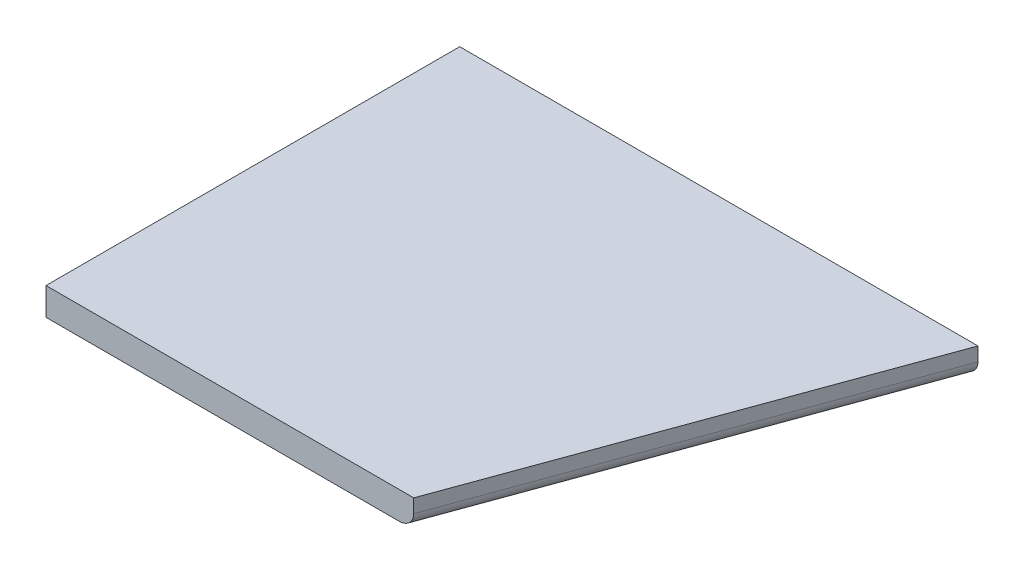
SolidWorks part; units mm, degrees
ref_plane "Front" through (0, 0, 0) normal (0, 0, 1) x (1, 0, 0)
ref_plane "Top" through (0, 0, 0) normal (0, 1, 0) x (1, 0, 0)
ref_plane "Right" through (0, 0, 0) normal (1, 0, 0) x (0, 0, -1)
sketch "Sketch1" plane through (0, 0, 0) normal (0, 1, 0) x (1, 0, 0)
  line L0 (0, 0) -> (32.7573, 90)
  line L1 (0, 0) -> (-80, 0)
  line L3 (0, 90) -> (-80, 90)
  line L4 (-80, 0) -> (-80, 90)
  line L5 (32.7573, 90) -> (0, 90)
  point P6 (0, 90)
  point P7 (0, 0)
  dimension "D1" = 80
  dimension "D2" = 90
  dimension "D3" = 110
extrude "Boss-Extrude1" add sketch "Sketch1" along normal blind 6
fillet "Fillet1" radius 3 1 edges at (16.3787, 0, -45)
